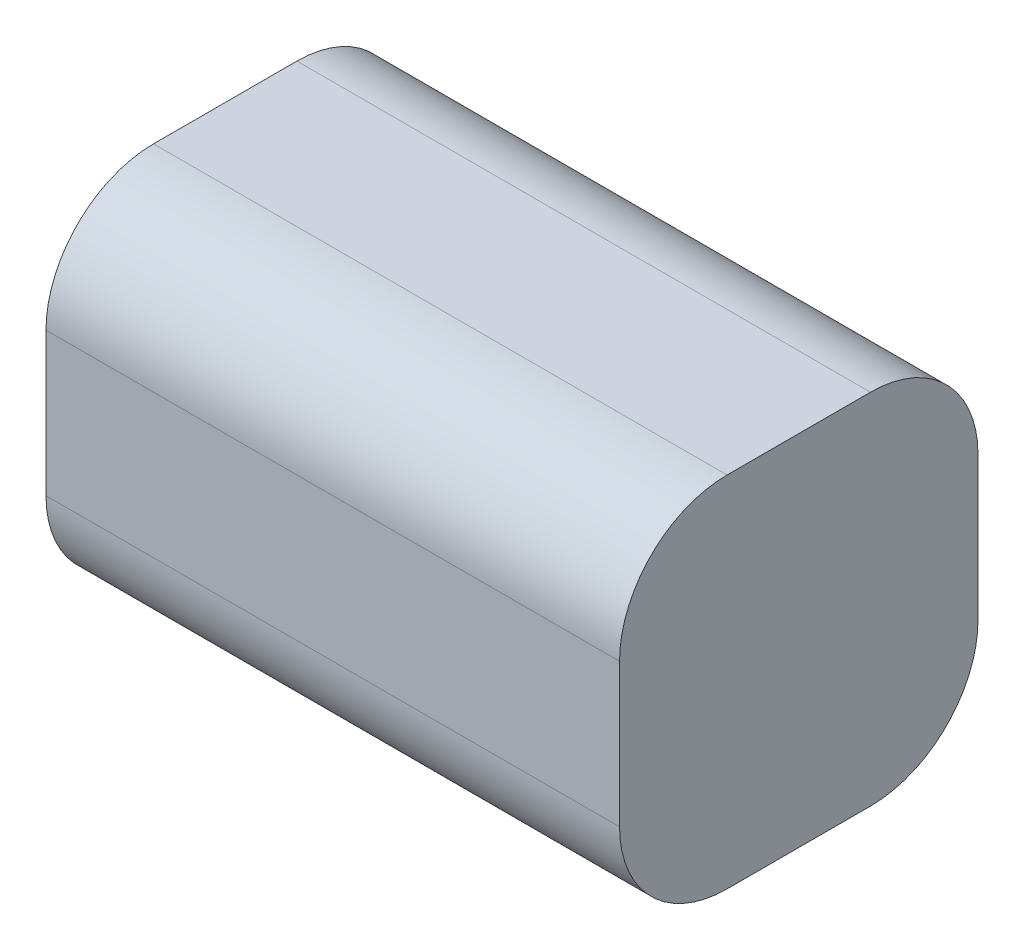
SolidWorks part; units mm, degrees
material "6061 合金"
ref_plane "前视基准面" through (0, 0, 0) normal (0, 0, 1) x (1, 0, 0)
ref_plane "上视基准面" through (0, 0, 0) normal (0, 1, 0) x (1, 0, 0)
ref_plane "右视基准面" through (0, 0, 0) normal (1, 0, 0) x (0, 0, -1)
sketch "草图1" plane through (0, 0, 0) normal (0, 0, 1) x (1, 0, 0)
  line L1 (-8, -5) -> (8, -5)
  line L2 (-8, -5) -> (-8, 5)
  line L3 (-8, 5) -> (8, 5)
  line L4 (8, -5) -> (8, 5)
  line L5 (-8, -5) -> (8, 5) construction
  line L6 (-8, 5) -> (8, -5) construction
  point P0 (0, 0)
  dimension "D1" = 10
  dimension "D2" = 16
extrude "凸台-拉伸1" add sketch "草图1" along normal blind 10
fillet "圆角1" radius 3 4 edges at (0, 5, 0) (0, -5, 0) (0, -5, 10) (0, 5, 10)
